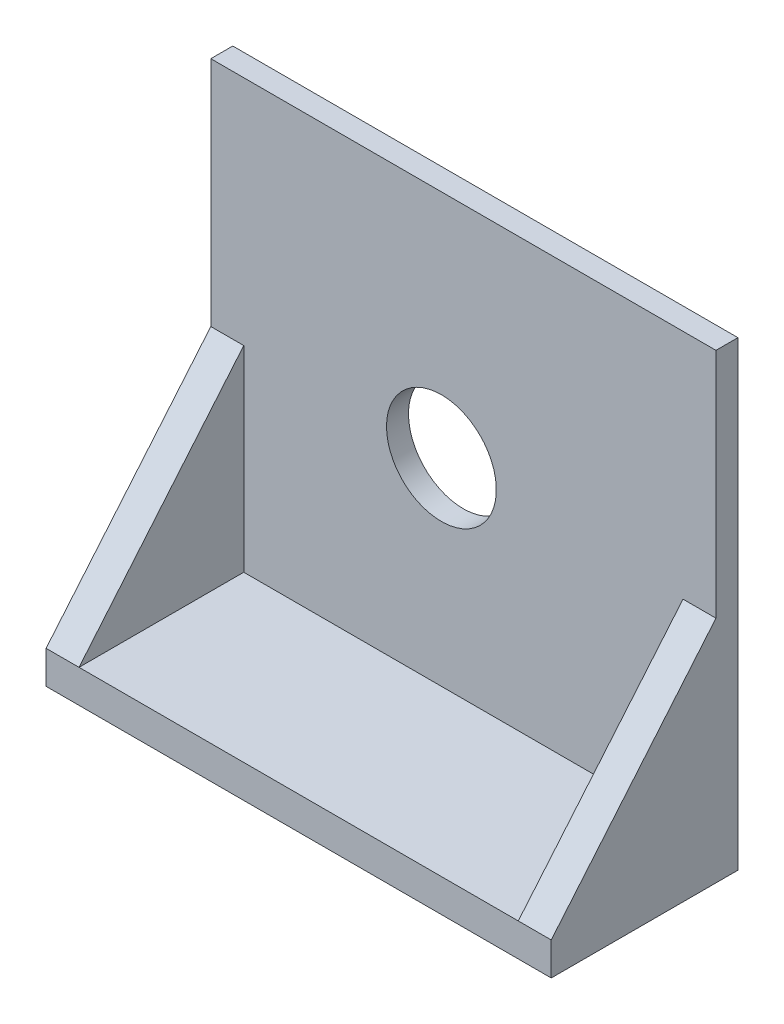
SolidWorks part; units mm, degrees
ref_plane "Front Plane" through (0, 0, 0) normal (0, 0, 1) x (1, 0, 0)
ref_plane "Top Plane" through (0, 0, 0) normal (0, 1, 0) x (1, 0, 0)
ref_plane "Right Plane" through (0, 0, 0) normal (1, 0, 0) x (0, 0, -1)
sketch "Sketch1" plane through (0, 0, 0) normal (0, 0, 1) x (1, 0, 0)
  line L1 (0, 0) -> (46, 0)
  line L2 (0, 0) -> (0, -42)
  line L3 (0, -42) -> (46, -42)
  line L4 (46, 0) -> (46, -42)
  dimension "D1" = 42
  dimension "D2" = 46
extrude "Boss-Extrude1" add sketch "Sketch1" along normal blind 2
sketch "Sketch2" plane through (0, 0, 2) normal (0, 0, 1) x (1, 0, 0)
  line L0 (46, -42) -> (46, 0) construction
  line L1 (0, -42) -> (46, -42)
  line L2 (0, -42) -> (0, -39)
  line L3 (0, -39) -> (46, -39)
  line L4 (46, -42) -> (46, -39)
  dimension "D1" = 3
extrude "Boss-Extrude2" add sketch "Sketch2" along normal blind 15
sketch "Sketch3" plane through (0, 0, 0) normal (0, 0, -1) x (-1, 0, 0)
  point P2 (0, 0)
sketch "Sketch4" plane through (0, 0, 0) normal (0, 0, -1) x (-1, 0, 0)
  line L0 (0, -42) -> (-46, -42) construction
  line L1 (-46, -42) -> (-46, 0) construction
  circle A0 centre (-21, -21) radius 5
  point P6 (-21.6468, -18.6996)
  point P7 (-20.9702, -14.6401)
  dimension "D3" = 10
  dimension "D1" = 21
  dimension "D2" = 25
extrude "Cut-Extrude2" cut sketch "Sketch4" against normal blind 2
sketch "Sketch5" plane through (0, 0, 0) normal (-1, 0, 0) x (0, 0, 1)
  line L0 (17, -39) -> (2, -21.1237)
  line L2 (17, -39) -> (2, -39) construction
  line L3 (17, -39) -> (2, -39)
  line L4 (2, 0) -> (2, -39) construction
  line L5 (2, -21.1237) -> (2, -39)
  point P6 (0, 0)
  dimension "D2" = 50
extrude "Boss-Extrude3" add sketch "Sketch5" against normal blind 3
sketch "Sketch6" plane through (46, 0, 0) normal (1, 0, 0) x (0, 0, -1)
  line L0 (-17, -39) -> (-2, -21.1237)
  line L1 (-2, -21.1237) -> (-2, -39) construction
  line L2 (-2, -39) -> (-2, 0) construction
  line L3 (-2, -21.1237) -> (-2, -39)
  line L4 (-2, -39) -> (-17, -39)
extrude "Boss-Extrude4" add sketch "Sketch6" against normal blind 3
